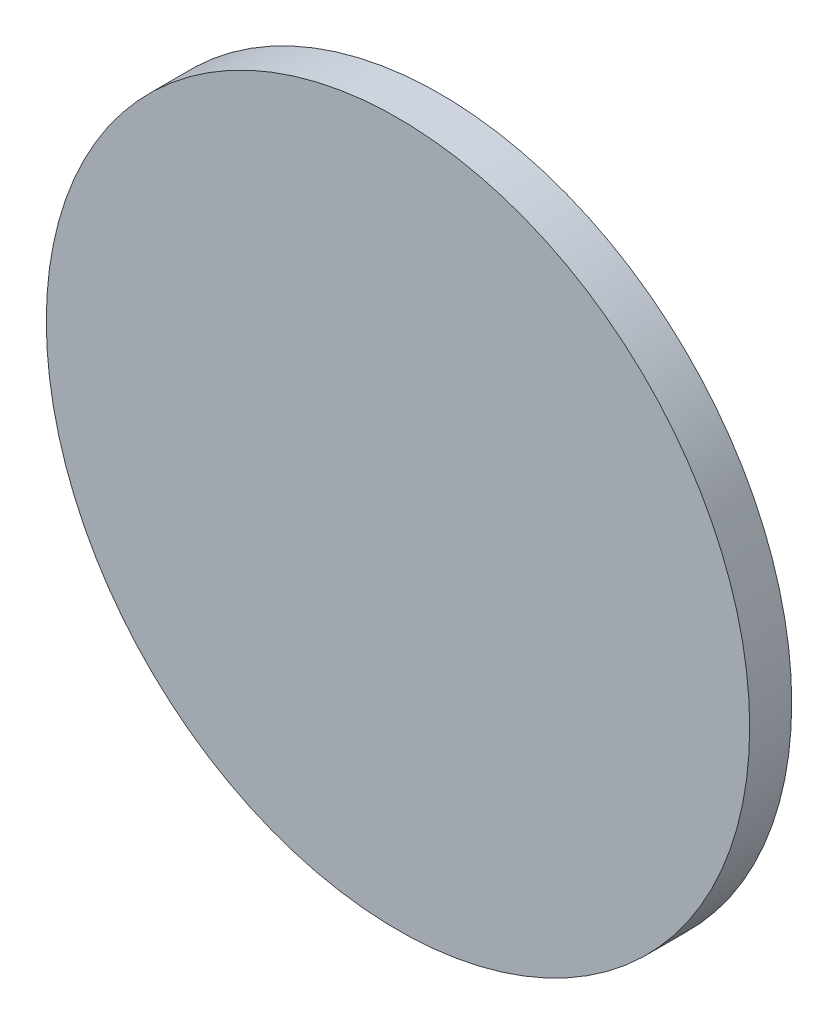
SolidWorks part; units mm, degrees
material "Acrylic (Medium-high impact)"
ref_plane "Front Plane" through (0, 0, 0) normal (0, 0, 1) x (1, 0, 0)
ref_plane "Top Plane" through (0, 0, 0) normal (0, 1, 0) x (1, 0, 0)
ref_plane "Right Plane" through (0, 0, 0) normal (1, 0, 0) x (0, 0, -1)
sketch "Sketch2" plane through (0, 0, 0) normal (0, 0, 1) x (1, 0, 0)
  circle A0 centre (0, 0) radius 25.1
  dimension "D1" = 50.2
extrude "Boss-Extrude1" add sketch "Sketch2" along normal blind 3
